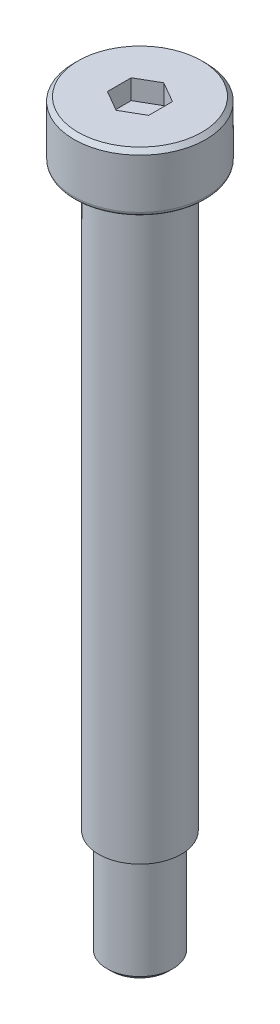
SolidWorks part; units mm, degrees
material "Plain Carbon Steel"
ref_plane "Front Plane" through (0, 0, 0) normal (0, 0, 1) x (1, 0, 0)
ref_plane "Top Plane" through (0, 0, 0) normal (0, 1, 0) x (1, 0, 0)
ref_plane "Right Plane" through (0, 0, 0) normal (1, 0, 0) x (0, 0, -1)
sketch "Sketch1" plane through (0, 0, 0) normal (0, 0, 1) x (1, 0, 0)
  line L0 (0, 0) -> (8, 0)
  line L1 (8, 0) -> (8, -7)
  line L2 (8, -7) -> (4.75, -7)
  line L3 (4.75, -7) -> (4.75, -7.5)
  line L4 (4.75, -7.5) -> (5, -7.5)
  line L5 (5, -7.5) -> (5, -77)
  line L6 (5, -77) -> (4, -77)
  line L7 (4, -77) -> (4, -90)
  line L8 (4, -90) -> (0, -90)
  line L9 (0, -90) -> (0, 0)
  line L10 (0, 5) -> (0, -95) construction
  dimension "D1" = 5
  dimension "D2" = 5
  dimension "D3" = 8
  dimension "D4" = 10
  dimension "D5" = 0.25
  dimension "D6" = 16
  dimension "D7" = 70
  dimension "D8" = 7
  dimension "D9" = 0.5
  dimension "D10" = 13
revolve "Revolve1" add sketch "Sketch1" angle 360 about L10
sketch "Sketch2" plane through (0, 0, 0) normal (0, 1, 0) x (1, 0, 0)
  line L1 (0, -2.8868) -> (2.5, -1.4434)
  line L2 (2.5, -1.4434) -> (2.5, 1.4434)
  line L3 (2.5, 1.4434) -> (0, 2.8868)
  line L4 (0, 2.8868) -> (-2.5, 1.4434)
  line L5 (-2.5, 1.4434) -> (-2.5, -1.4434)
  line L6 (-2.5, -1.4434) -> (0, -2.8868)
  circle A0 centre (0, 0) radius 2.5 construction
  dimension "D1" = 5
extrude "Cut-Extrude1" cut sketch "Sketch2" against normal blind 2.4
chamfer "Chamfer1" distance 0.5 angle 45 1 edges at (-8, 0, 0)
fillet "Fillet1" radius 0.5 1 edges at (-8, -7, 0)
chamfer "Chamfer2" distance 0.5 angle 45 1 edges at (-4, -90, 0)
